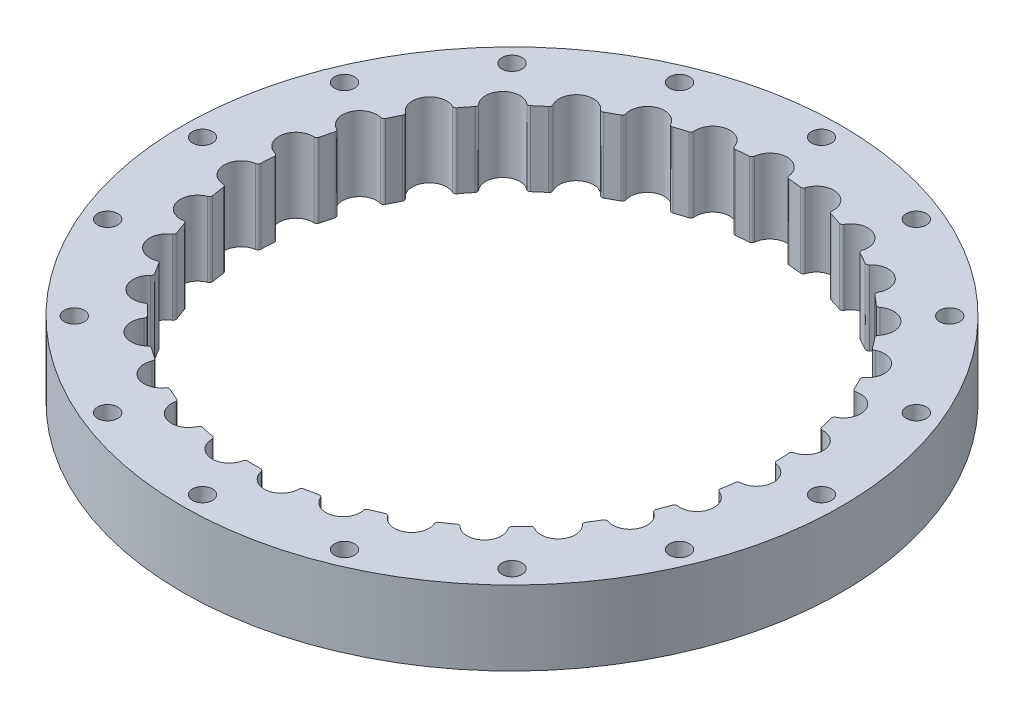
SolidWorks part; units mm, degrees
other "Markup1"
sketch "Sketch12" plane through (-57.5, 16, 57.5) normal (-0.5757, 0.7687, 0.2786) x (0.7628, 0.3823, 0.5216)
other "Markup2"
sketch "Sketch13" plane through (-57.5, 16, 57.5) normal (-0.5757, 0.7687, 0.2786) x (0.7628, 0.3823, 0.5216)
ref_plane "Front Plane" through (0, 0, 0) normal (0, 0, 1) x (1, 0, 0)
ref_plane "Top Plane" through (0, 0, 0) normal (0, 1, 0) x (1, 0, 0)
ref_plane "Right Plane" through (0, 0, 0) normal (1, 0, 0) x (0, 0, -1)
sketch "Sketch1" plane through (0, 0, 0) normal (0, 1, 0) x (1, 0, 0)
  line L0 (15.8389, 51.6249) -> (0, 0) construction
  line L1 (0, 0) -> (-4.5526, -44.7691) construction
  circle A0 centre (0, 0) radius 45
  circle A12 centre (0, 0) radius 57.5
  circle A13 centre (0, 0) radius 54 construction
  point P27 (0, 0)
  point P54 (0, 0)
  dimension "D1" = 90
  dimension "D4" = 115
  dimension "D5" = 108
  dimension "D8" = 11.25
extrude "Boss-Extrude1" add sketch "Sketch1" along normal blind 13
sketch "Sketch2" plane through (0, 0, 0) normal (0, -1, 0) x (1, 0, 0)
  circle A0 centre (0, 0) radius 57.5
  circle A1 centre (0, 0) radius 45
extrude "Boss-Extrude2" add sketch "Sketch2" along normal blind 1
sketch "Sketch3" plane through (0, -1, 0) normal (0, -1, 0) x (1, 0, 0)
  circle A0 centre (0, 0) radius 57.5
  circle A1 centre (0, 0) radius 42.5
  dimension "D1" = 85
extrude "Boss-Extrude3" add sketch "Sketch3" along normal blind 2
sketch "Sketch5" plane through (0, 13, 0) normal (0, 1, 0) x (1, 0, 0)
  circle A0 centre (0, 45) radius 3
  circle A1 centre (0, 0) radius 45 construction
  circle A2 centre (0, 0) radius 45 construction
  dimension "D1" = 6
extrude "Cut-Extrude2" cut sketch "Sketch5" against normal blind 13
fillet "Fillet4" radius 0.5 2 edges at (2.9983, 6.5, -44.9) (-2.9983, 6.5, -44.9)
sketch "Sketch10" plane through (0, 13, 0) normal (0, 1, 0) x (1, 0, 0)
  circle A0 centre (0, 0) radius 45
  circle A1 centre (0, 0) radius 57.5
extrude "Boss-Extrude4" add sketch "Sketch10" along normal blind 1
sketch "Sketch11" plane through (0, 14, 0) normal (0, 1, 0) x (1, 0, 0)
  circle A0 centre (0, 0) radius 42.5
  circle A1 centre (0, 0) radius 57.5
extrude "Boss-Extrude5" add sketch "Sketch11" along normal blind 2
sketch "Sketch7" plane through (0, 16, 0) normal (0, 1, 0) x (1, 0, 0)
  circle A0 centre (0, 45) radius 1.75
  arc A1 (3.4425, 44.8681) -> (-3.4425, 44.8681) centre (0, 0) ccw construction
  dimension "D1" = 3.5
extrude "Cut-Extrude3" cut sketch "Sketch7" against normal blind 23
pattern_circular "CirPattern3" count 31 over 360 about axis through (0, 0, 0) along (0, 1, 0) of "Cut-Extrude2", "Fillet4", "Cut-Extrude3"
sketch "Sketch4" plane through (0, 16, 0) normal (0, 1, 0) x (1, 0, 0)
  circle A0 centre (0, 0) radius 54 construction
  circle A1 centre (0, 54) radius 1.75
  circle A2 centre (20.6649, 49.8895) radius 1.75
  circle A3 centre (38.1838, 38.1838) radius 1.75
  circle A4 centre (49.8895, 20.6649) radius 1.75
  circle A5 centre (54, 0) radius 1.75
  circle A6 centre (49.8895, -20.6649) radius 1.75
  circle A7 centre (38.1838, -38.1838) radius 1.75
  circle A8 centre (20.6649, -49.8895) radius 1.75
  circle A9 centre (0, -54) radius 1.75
  circle A10 centre (-20.6649, -49.8895) radius 1.75
  circle A11 centre (-38.1838, -38.1838) radius 1.75
  circle A12 centre (-49.8895, -20.6649) radius 1.75
  circle A13 centre (-54, 0) radius 1.75
  circle A14 centre (-49.8895, 20.6649) radius 1.75
  circle A15 centre (-38.1838, 38.1838) radius 1.75
  circle A16 centre (-20.6649, 49.8895) radius 1.75
  circle A17 centre (0, 0) radius 45 construction
  point P38 (0, 0)
  point P102 (0, 0)
  dimension "D1" = 108
  dimension "D2" = 3.5
extrude "Cut-Extrude1" cut sketch "Sketch4" against normal blind 51
sketch "Sketch15" plane through (0, 0, 0) normal (0, 1, 0) x (1, 0, 0)
  circle A0 centre (0, 0) radius 106.0792
extrude "Cut-Extrude5" cut sketch "Sketch15" against normal blind 10
sketch "Sketch16" plane through (0, 13, 0) normal (0, -1, 0) x (1, 0, 0)
  circle A0 centre (0, 0) radius 89.8068
extrude "Cut-Extrude6" cut sketch "Sketch16" against normal blind 10
